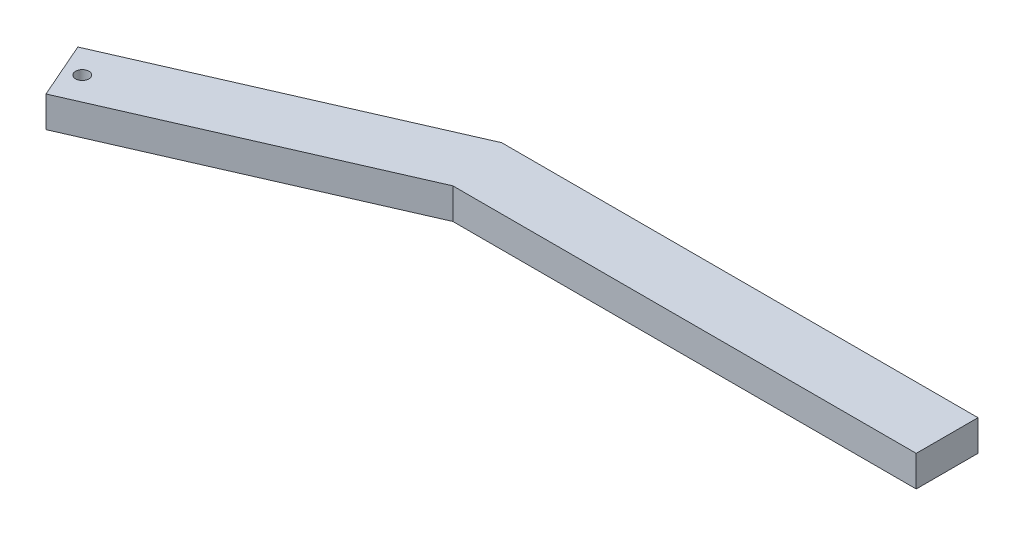
SolidWorks part; units mm, degrees
ref_plane "Front Plane" through (0, 0, 0) normal (0, 0, 1) x (1, 0, 0)
ref_plane "Top Plane" through (0, 0, 0) normal (0, 1, 0) x (1, 0, 0)
ref_plane "Right Plane" through (0, 0, 0) normal (1, 0, 0) x (0, 0, -1)
sketch "Sketch1" plane through (0, 0, 0) normal (0, 1, 0) x (1, 0, 0)
  line L0 (0, 0) -> (242.4215, 106.1223)
  line L1 (242.4215, 106.1223) -> (634.0535, 106.1223)
  line L2 (634.0535, 106.1223) -> (634.0535, 55.3223)
  line L3 (634.0535, 55.3223) -> (253.0535, 55.3223)
  line L4 (253.0535, 55.3223) -> (20.3717, -46.5364)
  line L5 (20.3717, -46.5364) -> (0, 0)
  dimension "D1" = 381
  dimension "D2" = 254
  dimension "D3" = 50.8
  dimension "D4" = 50.8
extrude "Boss-Extrude1" add sketch "Sketch1" along normal blind 25.4
hole_wizard "CSK for M10 Countersunk Flat Head Screw1" positions "Sketch4" profile "Sketch5" countersink size "M10" standard "DIN" end condition through all
sketch "Sketch4" plane through (0, 0, 0) normal (0, 1, 0) x (1, 0, 0)
  line L0 (10.1859, -23.2682) -> (56.9634, -2.7909) construction
  line L1 (0, 0) -> (20.3717, -46.5364) construction
  line L2 (0, 0) -> (20.3717, -46.5364) construction
  point P0 (21.82, -18.1752)
  point P11 (57.1976, -3.3345)
  dimension "D1" = 12.7
sketch "Sketch5" plane through (21.82, 0, 18.1752) normal (1, 0, 0) x (0, 0, -1)
  line L0 (0, 0) -> (0, 25.4)
  line L1 (0, 25.4) -> (5.5, 25.4)
  line L2 (5.5, 25.4) -> (5.5, 4.5)
  line L3 (5.5, 4.5) -> (10, 0)
  line L5 (10, 0) -> (0, 0)
  line L6 (-5.5, 4.5) -> (-10, 0) construction
  line L11 (0, -6.35) -> (0, 107.95) construction
  dimension "Thru Hole Dia." = 11
  dimension "Thru Hole Depth" = 25.4
  dimension "Near C'Sink Dia." = 20
  dimension "Near C'Sink Angle" = 90
